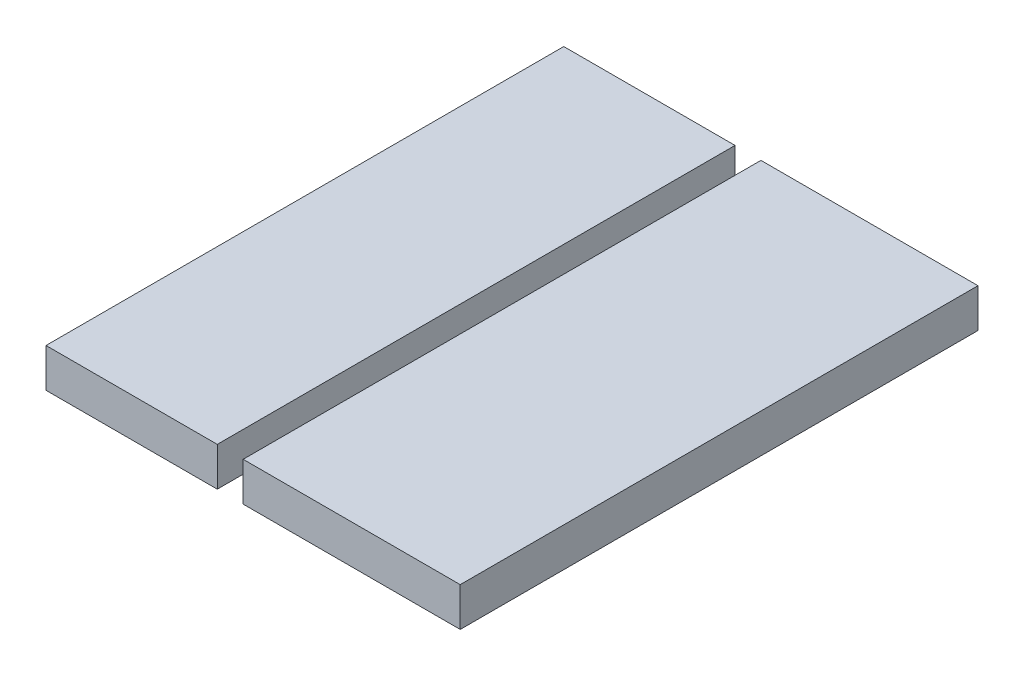
SolidWorks part; units mm, degrees
ref_plane "Front Plane" through (0, 0, 0) normal (0, 0, 1) x (1, 0, 0)
ref_plane "Top Plane" through (0, 0, 0) normal (0, 1, 0) x (1, 0, 0)
ref_plane "Right Plane" through (0, 0, 0) normal (1, 0, 0) x (0, 0, -1)
sketch "Sketch1" plane through (0, 0, 0) normal (0, 1, 0) x (1, 0, 0)
  line L1 (28.2086, 23.1049) -> (-22.5914, 23.1049)
  line L2 (28.2086, 23.1049) -> (28.2086, -40.3951)
  line L3 (28.2086, -40.3951) -> (-22.5914, -40.3951)
  line L4 (-22.5914, 23.1049) -> (-22.5914, -40.3951)
  dimension "D1" = 50.8
  dimension "D2" = 63.5
extrude "Boss-Extrude1" add sketch "Sketch1" along normal blind 4.7625
sketch "Sketch2" plane through (0, 4.7625, 0) normal (0, 1, 0) x (1, 0, 0)
  line L0 (28.2086, 23.1049) -> (-22.5914, 23.1049) construction
  line L1 (-1.5875, 23.1049) -> (1.5875, 23.1049)
  line L2 (-1.5875, 23.1049) -> (-1.5875, -40.3951)
  line L3 (-1.5875, -40.3951) -> (1.5875, -40.3951)
  line L4 (1.5875, 23.1049) -> (1.5875, -40.3951)
  line L5 (-22.5914, -40.3951) -> (28.2086, -40.3951) construction
  dimension "D1" = 3.175
  dimension "D2" = 1.5875
extrude "Cut-Extrude1" cut sketch "Sketch2" against normal blind 10
